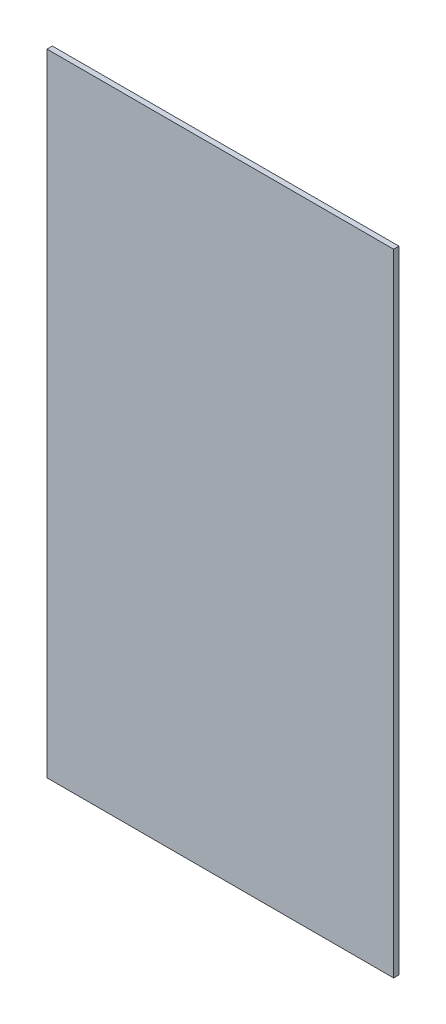
SolidWorks part; units mm, degrees
ref_plane "Přední rovina" through (0, 0, 0) normal (0, 0, 1) x (1, 0, 0)
ref_plane "Horní rovina" through (0, 0, 0) normal (0, 1, 0) x (1, 0, 0)
ref_plane "Pravá rovina" through (0, 0, 0) normal (1, 0, 0) x (0, 0, -1)
sketch "Skica1" plane through (0, 0, 0) normal (0, 0, 1) x (1, 0, 0)
  line L1 (-97.5, 177.5) -> (97.5, 177.5)
  line L2 (-97.5, 177.5) -> (-97.5, -177.5)
  line L3 (-97.5, -177.5) -> (97.5, -177.5)
  line L4 (97.5, 177.5) -> (97.5, -177.5)
  line L5 (-97.5, 177.5) -> (97.5, -177.5) construction
  line L6 (-97.5, -177.5) -> (97.5, 177.5) construction
  point P0 (0, 0)
  dimension "D1" = 195
  dimension "D2" = 355
extrude "Přidat vysunutím1" add sketch "Skica1" along normal blind 3
